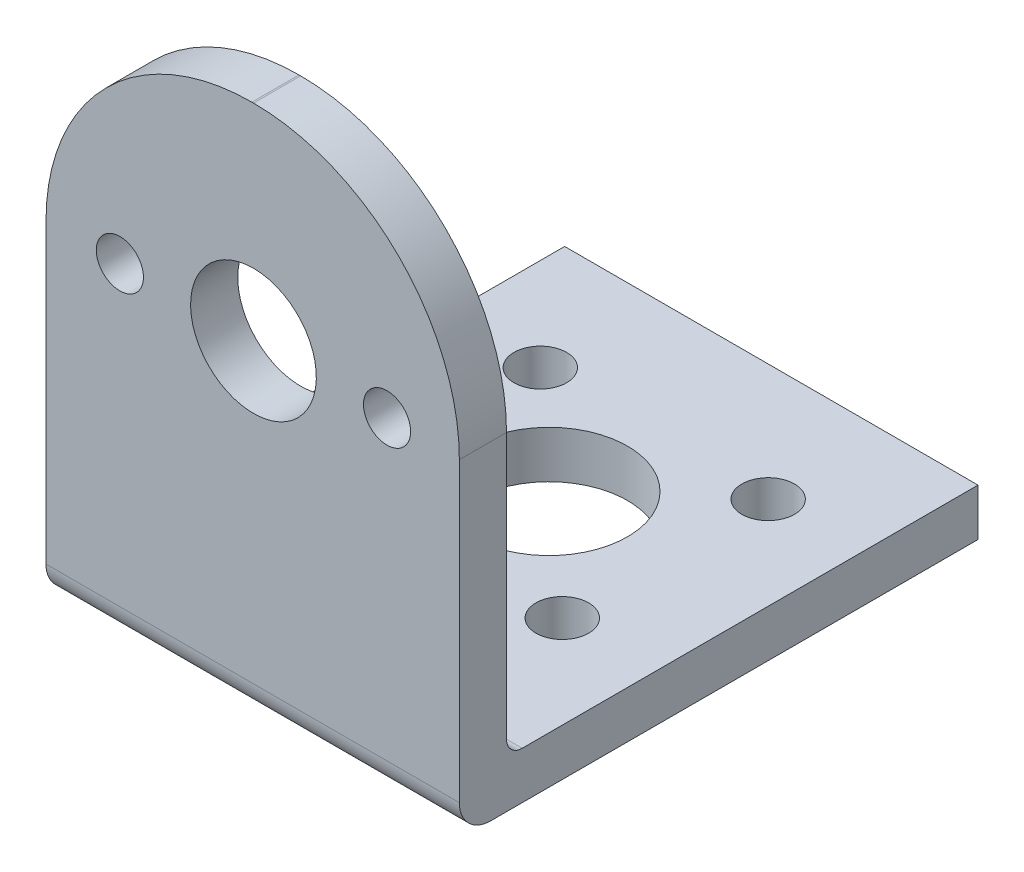
SolidWorks part; units mm, degrees
ref_plane "Alzado" through (0, 0, 0) normal (0, 0, 1) x (1, 0, 0)
ref_plane "Planta" through (0, 0, 0) normal (0, 1, 0) x (1, 0, 0)
ref_plane "Vista lateral" through (0, 0, 0) normal (1, 0, 0) x (0, 0, -1)
sketch "Croquis1" plane through (0, 0, 0) normal (1, 0, 0) x (0, 0, -1)
  line L0 (-17.25, 28.9844) -> (-14.25, 28.9844)
  line L1 (-14.25, 28.9844) -> (-14.25, -2.0156)
  line L2 (-14.25, -2.0156) -> (15.75, -2.0156)
  line L3 (15.75, -2.0156) -> (15.75, -5.0156)
  line L4 (15.75, -5.0156) -> (-17.25, -5.0156)
  line L5 (-17.25, -5.0156) -> (-17.25, 28.9844)
  dimension "D1" = 3
  dimension "D2" = 3
  dimension "D3" = 33
  dimension "D4" = 34
extrude "Saliente-Extruir1" add sketch "Croquis1" along normal blind 26.3
fillet "Redondeo1" radius 1 1 edges at (13.15, -2.0156, 14.25)
fillet "Redondeo2" radius 2 1 edges at (13.15, -5.0156, 17.25)
fillet "Redondeo3" radius 13.1 2 edges at (0, 28.9844, 15.75) (26.3, 28.9844, 15.75)
sketch "Croquis2" plane through (0, -2.0156, 0) normal (0, 1, 0) x (1, 0, 0)
  line L0 (26.3, 15.75) -> (0, 15.75) construction
  line L1 (0, 15.75) -> (0, -13.25) construction
  line L2 (26.3, 15.75) -> (26.3, -13.25) construction
  line L4 (29.2397, 1.75) -> (-3.2397, 1.75) construction
  circle A0 centre (13, 1.75) radius 5
  circle A1 centre (5.9, 8.3) radius 1.675
  circle A2 centre (20.4, 8.3) radius 1.675
  circle A5 centre (20.4, -4.8) radius 1.675
  circle A6 centre (5.9, -4.8) radius 1.675
  point P13 (13, 1.75)
  dimension "D1" = 10
  dimension "D4" = 3.35
  dimension "D2" = 14
  dimension "D3" = 13
  dimension "D5" = 7.45
  dimension "D6" = 5.9
  dimension "D7" = 5.9
  dimension "D8" = 14.5
extrude "Cortar-Extruir1" cut sketch "Croquis2" against normal through all
sketch "Croquis3" plane through (0, 0, 14.25) normal (0, 0, -1) x (-1, 0, 0)
  line L0 (2.9481, 15.8844) -> (-29.3481, 15.8844) construction
  circle A0 centre (-13.2, 15.8844) radius 4
  arc A1 (-13.2, 28.9844) -> (-26.3, 15.8844) centre (-13.2, 15.8844) ccw construction
  circle A2 centre (-21.7, 15.8844) radius 1.5
  circle A3 centre (-4.7, 15.8844) radius 1.5
  point P8 (-13.2, 15.8844)
  dimension "D1" = 8
  dimension "D2" = 3
  dimension "D3" = 8.5
  dimension "D4" = 8.5
extrude "Cortar-Extruir2" cut sketch "Croquis3" against normal through all
